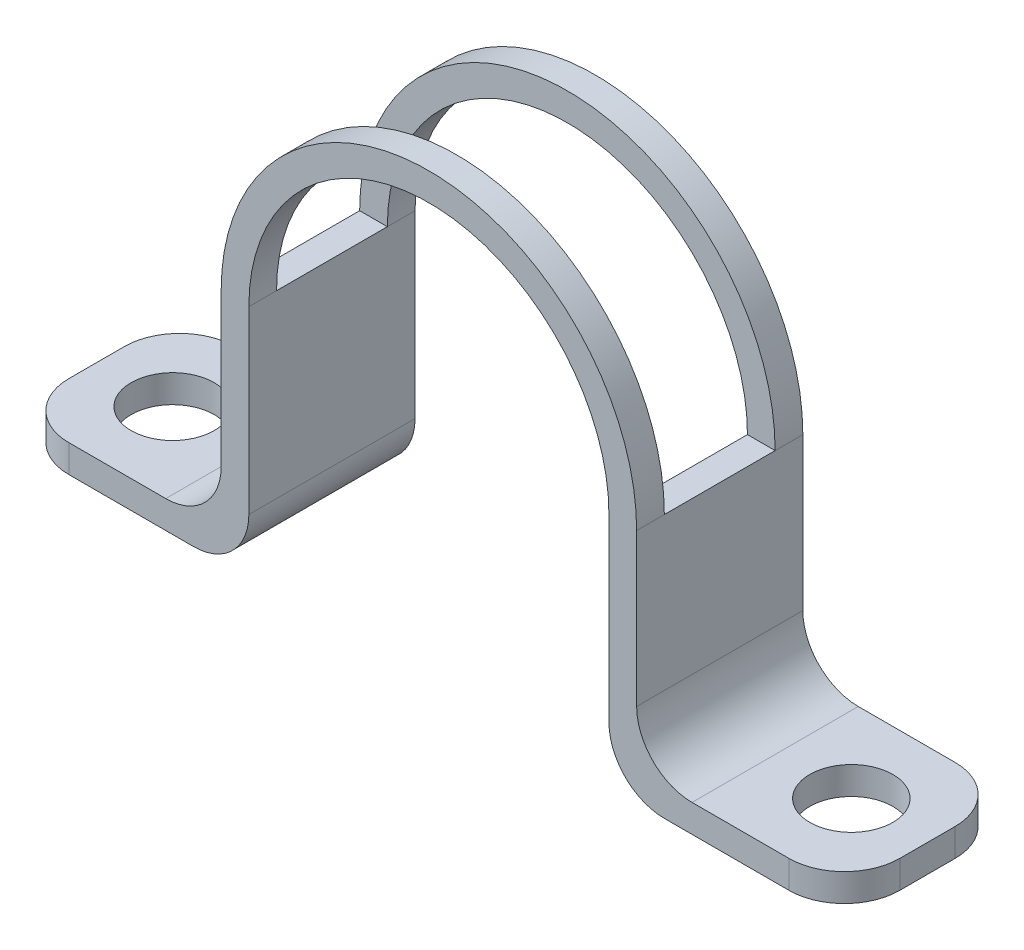
SolidWorks part; units mm, degrees
ref_plane "Front Plane" through (0, 0, 0) normal (0, 0, 1) x (1, 0, 0)
ref_plane "Top Plane" through (0, 0, 0) normal (0, 1, 0) x (1, 0, 0)
ref_plane "Right Plane" through (0, 0, 0) normal (1, 0, 0) x (0, 0, -1)
sketch "Sketch1" plane through (0, 0, 0) normal (0, 0, 1) x (1, 0, 0)
  line L0 (-15, 0) -> (-9.5, 0)
  line L1 (-7.5, 2) -> (-7.5, 7.5)
  line L2 (-6.5, 7.5) -> (-6.5, 1)
  line L3 (-8.5, -1) -> (-15, -1)
  line L4 (-15, -1) -> (-15, 0)
  line L5 (0, 17.0927) -> (0, -16.3229) construction
  line L6 (15, -1) -> (15, 0)
  line L7 (8.5, -1) -> (15, -1)
  line L8 (6.5, 7.5) -> (6.5, 1)
  line L9 (7.5, 2) -> (7.5, 7.5)
  line L10 (15, 0) -> (9.5, 0)
  arc A0 (7.5, 7.5) -> (-7.5, 7.5) centre (0, 7.5) ccw
  arc A1 (6.5, 7.5) -> (-6.5, 7.5) centre (0, 7.5) ccw
  arc A2 (-6.5, 1) -> (-8.5, -1) centre (-8.5, 1) cw
  arc A3 (-9.5, 0) -> (-7.5, 2) centre (-9.5, 2) ccw
  arc A4 (6.5, 1) -> (8.5, -1) centre (8.5, 1) ccw
  arc A5 (9.5, 0) -> (7.5, 2) centre (9.5, 2) cw
  dimension "D1" = 15
  dimension "D2" = 13
  dimension "D8" = 2
  dimension "D3" = 1
  dimension "D4" = 15
  dimension "D5" = 1
  dimension "D6" = 6.5
  dimension "D7" = 8.5
extrude "Boss-Extrude1" add sketch "Sketch1" along normal blind 6
sketch "Sketch2" plane through (0, 0, 0) normal (0, 1, 0) x (1, 0, 0)
  line L0 (9.5, 0) -> (15, -6) construction
  line L1 (15, -6) -> (15, 0) construction
  line L2 (15, 0) -> (9.5, -6) construction
  line L3 (0, 8.7107) -> (0, -12.6984) construction
  circle A0 centre (12.25, -3) radius 1.5
  circle A1 centre (-12.25, -3) radius 1.5
  dimension "D1" = 3
extrude "Cut-Extrude1" cut sketch "Sketch2" against normal blind 6
sketch "Sketch3" plane through (0, 0, 0) normal (1, 0, 0) x (0, 0, -1)
  line L0 (-5, 17.5) -> (-5, 7.5)
  line L1 (-5, 7.5) -> (-1, 7.5)
  line L2 (-1, 7.5) -> (-1, 17.5)
  line L3 (-1, 17.5) -> (-5, 17.5)
  line L4 (-6, -1) -> (0, -1) construction
  line L5 (-6, 15) -> (-6, 7.5) construction
  dimension "D1" = 4
  dimension "D2" = 8.5
  dimension "D3" = 1
  dimension "D4" = 10
extrude "Cut-Extrude2" cut sketch "Sketch3" against normal blind 17 and the other way blind 12
fillet "Fillet1" radius 2 4 edges at (15, -0.5, 0) (15, -0.5, 6) (-15, -0.5, 0) (-15, -0.5, 6)
